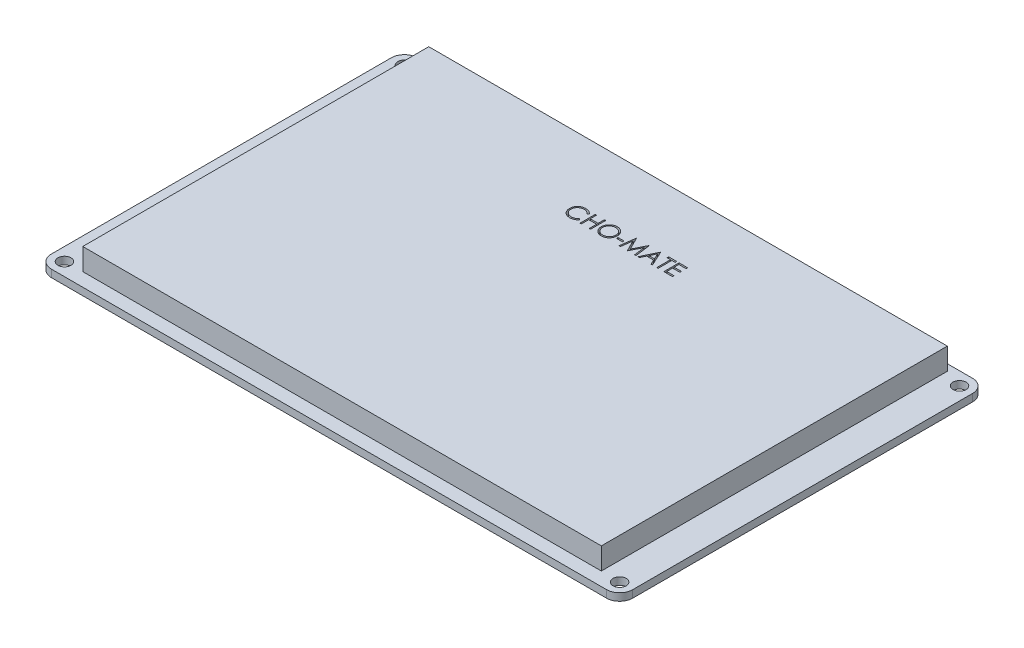
SolidWorks part; units mm, degrees
ref_plane "Front Plane" through (0, 0, 0) normal (0, 0, 1) x (1, 0, 0)
ref_plane "Top Plane" through (0, 0, 0) normal (0, 1, 0) x (1, 0, 0)
ref_plane "Right Plane" through (0, 0, 0) normal (1, 0, 0) x (0, 0, -1)
sketch "Sketch1" plane through (0, 0, 0) normal (0, 1, 0) x (1, 0, 0)
  line L1 (-1336.9, 893.1) -> (-1203.5, 893.1)
  line L2 (-1336.9, 893.1) -> (-1336.9, 809.1)
  line L3 (-1336.9, 809.1) -> (-1203.5, 809.1)
  line L4 (-1203.5, 893.1) -> (-1203.5, 809.1)
  circle A0 centre (-1333.9, 890.1) radius 1.5
  circle A1 centre (-1206.5, 890.1) radius 1.5
  circle A2 centre (-1206.5, 812.1) radius 1.5
  circle A3 centre (-1333.9, 812.1) radius 1.5
  dimension "D5" = 3
  dimension "D6" = 3
  dimension "D7" = 3
  dimension "D11" = 3
  dimension "D14" = 3
  dimension "D1" = 133.4
  dimension "D2" = 84
  dimension "D3" = 3
  dimension "D4" = 3
  dimension "D8" = 3
  dimension "D9" = 3
  dimension "D10" = 3
  dimension "D12" = 3
  dimension "D13" = 3
extrude "Boss-Extrude1" add sketch "Sketch1" along normal blind 1.7
sketch "Sketch2" plane through (0, 1.7, 0) normal (0, 1, 0) x (1, 0, 0)
  line L0 (-1203.5, 809.1) -> (-1203.5, 893.1) construction
  line L1 (-1329.8, 891.6) -> (-1210.8, 891.6)
  line L2 (-1329.8, 891.6) -> (-1329.8, 812.2)
  line L3 (-1329.8, 812.2) -> (-1210.8, 812.2)
  line L4 (-1210.8, 891.6) -> (-1210.8, 812.2)
  line L5 (-1336.9, 809.1) -> (-1203.5, 809.1) construction
  line L6 (-1203.5, 893.1) -> (-1336.9, 893.1) construction
  line L7 (-1336.9, 893.1) -> (-1336.9, 809.1) construction
  dimension "D1" = 7.3
  dimension "D2" = 3.1
  dimension "D3" = 1.5
  dimension "D4" = 7.1
extrude "Boss-Extrude2" add sketch "Sketch2" along normal blind 5
sketch "Sketch3" plane through (0, 0, 0) normal (0, -1, 0) x (1, 0, 0)
  line L0 (-1336.9, -893.1) -> (-1336.9, -809.1) construction
  line L1 (-1336.9, -860.1) -> (-1328.4, -860.1)
  line L2 (-1336.9, -860.1) -> (-1336.9, -842.5)
  line L3 (-1336.9, -842.5) -> (-1328.4, -842.5)
  line L4 (-1328.4, -860.1) -> (-1328.4, -842.5)
  line L5 (-1203.5, -893.1) -> (-1336.9, -893.1) construction
  line L6 (-1336.9, -809.1) -> (-1203.5, -809.1) construction
  dimension "D1" = 33
  dimension "D2" = 33.4
  dimension "D3" = 8.5
extrude "Boss-Extrude3" add sketch "Sketch3" along normal blind 7.9
sketch "Sketch4" plane through (0, 6.7, 0) normal (0, 1, 0) x (1, 0, 0)
  text T0 "CHO-MATE"
extrude "Cut-Extrude1" cut sketch "Sketch4" against normal blind 1
fillet "Fillet1" radius 3 4 edges at (-1203.5, 0.85, -893.1) (-1203.5, 0.85, -809.1) (-1336.9, 0.85, -809.1) (-1336.9, 0.85, -893.1)
